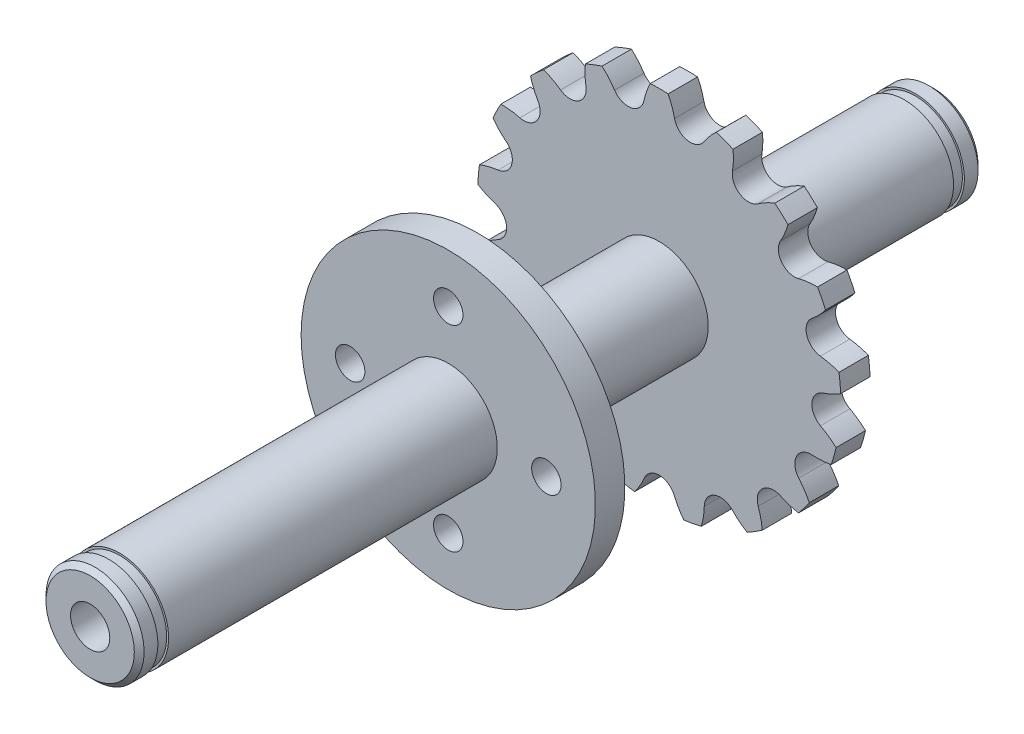
SolidWorks part; units mm, degrees
material "合金钢"
ref_plane "前视基准面" through (0, 0, 0) normal (0, 0, 1) x (1, 0, 0)
ref_plane "上视基准面" through (0, 0, 0) normal (0, 1, 0) x (1, 0, 0)
ref_plane "右视基准面" through (0, 0, 0) normal (1, 0, 0) x (0, 0, -1)
sketch "草图1" plane through (0, 0, 0) normal (0, 0, 1) x (1, 0, 0)
  line L0 (0, 15.63) -> (0, 27.7184) construction
  line L1 (2.872, 15.3639) -> (4.904, 26.2342) construction
  line L2 (-2.872, 15.3639) -> (-4.904, 26.2342) construction
  line L3 (-3.175, 16.9847) -> (3.175, 16.9847) construction
  line L4 (3.175, 16.9847) -> (-13.356, 13.4532) construction
  line L5 (3.175, 16.9847) -> (-5.7966, 15.0682) construction
  circle A0 centre (0, 0) radius 17.279 construction
  arc A1 (-11.7798, 14.2714) -> (-13.1236, 13.0463) centre (0, 0) ccw
  circle A2 centre (0, 0) radius 15.63 construction
  arc A5 (1.5624, 16.6403) -> (0.9092, 18.4826) centre (-5.7966, 15.0682) ccw
  arc A6 (1.5624, 16.6403) -> (2.872, 15.3639) centre (3.175, 16.9847) ccw
  arc A7 (-1.5624, 16.6403) -> (-0.9092, 18.4826) centre (5.7966, 15.0682) cw
  arc A8 (-1.5624, 16.6403) -> (-2.872, 15.3639) centre (-3.175, 16.9847) cw
  arc A9 (4.5542, 16.081) -> (5.8289, 17.563) centre (10.8484, 11.9567) cw
  arc A10 (4.5542, 16.081) -> (2.872, 15.3639) centre (3.175, 16.9847) cw
  arc A11 (7.4681, 14.9522) -> (8.2281, 13.2889) centre (9.0962, 14.6909) ccw
  arc A12 (7.4681, 14.9522) -> (7.5245, 16.9061) centre (0.0381, 16.1446) ccw
  arc A13 (10.0558, 13.3499) -> (11.7798, 14.2714) centre (14.4351, 7.2304) cw
  arc A14 (10.0558, 13.3499) -> (8.2281, 13.2889) centre (9.0962, 14.6909) cw
  arc A15 (12.3651, 11.2447) -> (12.473, 9.4192) centre (13.7889, 10.4129) ccw
  arc A16 (12.3651, 11.2447) -> (13.1236, 13.0463) centre (5.8676, 15.0406) ccw
  arc A17 (14.1993, 8.8158) -> (16.1397, 9.0523) centre (16.0722, 1.5276) cw
  arc A18 (14.1993, 8.8158) -> (12.473, 9.4192) centre (13.7889, 10.4129) cw
  arc A19 (15.5922, 6.0186) -> (15.0333, 4.2774) centre (16.6193, 4.7286) ccw
  arc A20 (15.5922, 6.0186) -> (16.9503, 7.4245) centre (10.9047, 11.9053) ccw
  arc A21 (16.4251, 3.0911) -> (18.3199, 2.6107) centre (15.5387, -4.3815) cw
  arc A22 (16.4251, 3.0911) -> (15.0333, 4.2774) centre (16.6193, 4.7286) cw
  arc A23 (16.7134, -0.0204) -> (15.5633, -1.4422) centre (17.2052, -1.5943) ccw
  arc A24 (16.7134, -0.0204) -> (18.4877, 0.8) centre (14.469, 7.1622) ccw
  arc A25 (16.4326, -3.051) -> (18.0259, -4.1835) centre (12.9066, -9.6989) cw
  arc A26 (16.4326, -3.051) -> (15.5633, -1.4422) centre (17.2052, -1.5943) cw
  arc A27 (15.5774, -6.0566) -> (13.9914, -6.9669) centre (15.4675, -7.7019) ccw
  arc A28 (15.5774, -6.0566) -> (17.5283, -5.9325) centre (16.0792, 1.4517) ccw
  arc A29 (14.2208, -8.7811) -> (15.2974, -10.4127) centre (8.5314, -13.7064) cw
  arc A30 (14.2208, -8.7811) -> (13.9914, -6.9669) centre (15.4675, -7.7019) cw
  arc A31 (12.3376, -11.2748) -> (10.5299, -11.5507) centre (11.6408, -12.7693) ccw
  arc A32 (12.3376, -11.2748) -> (14.2015, -11.8639) centre (15.5179, -4.4548) ccw
  arc A33 (10.0884, -13.3253) -> (10.5029, -15.2356) centre (3.004, -15.8627) cw
  arc A34 (10.0884, -13.3253) -> (10.5299, -11.5507) centre (11.6408, -12.7693) cw
  arc A35 (7.4316, -14.9703) -> (5.6462, -14.5745) centre (6.2419, -16.1121) ccw
  arc A36 (7.4316, -14.9703) -> (8.9568, -16.1929) centre (12.8607, -9.7597) ccw
  arc A37 (4.5935, -16.0698) -> (4.2899, -18.0009) centre (-2.9291, -15.8767) cw
  arc A38 (4.5935, -16.0698) -> (5.6462, -14.5745) centre (6.2419, -16.1121) cw
  arc A39 (1.5218, -16.644) -> (0, -15.63) centre (0, -17.279) ccw
  arc A40 (1.5218, -16.644) -> (2.5024, -18.335) centre (8.4666, -13.7465) ccw
  arc A41 (-1.5218, -16.644) -> (-2.5024, -18.335) centre (-8.4666, -13.7465) cw
  arc A42 (-1.5218, -16.644) -> (0, -15.63) centre (0, -17.279) cw
  arc A43 (-4.5935, -16.0698) -> (-5.6462, -14.5745) centre (-6.2419, -16.1121) ccw
  arc A44 (-4.5935, -16.0698) -> (-4.2899, -18.0009) centre (2.9291, -15.8767) ccw
  arc A45 (-7.4316, -14.9703) -> (-8.9568, -16.1929) centre (-12.8607, -9.7597) cw
  arc A46 (-7.4316, -14.9703) -> (-5.6462, -14.5745) centre (-6.2419, -16.1121) cw
  arc A47 (-10.0884, -13.3253) -> (-10.5299, -11.5507) centre (-11.6408, -12.7693) ccw
  arc A48 (-10.0884, -13.3253) -> (-10.5029, -15.2356) centre (-3.004, -15.8627) ccw
  arc A49 (-12.3376, -11.2748) -> (-14.2015, -11.8639) centre (-15.5179, -4.4548) cw
  arc A50 (-12.3376, -11.2748) -> (-10.5299, -11.5507) centre (-11.6408, -12.7693) cw
  arc A51 (-14.2208, -8.7811) -> (-13.9914, -6.9669) centre (-15.4675, -7.7019) ccw
  arc A52 (-14.2208, -8.7811) -> (-15.2974, -10.4127) centre (-8.5314, -13.7064) ccw
  arc A53 (-15.5774, -6.0566) -> (-17.5283, -5.9325) centre (-16.0792, 1.4517) cw
  arc A54 (-15.5774, -6.0566) -> (-13.9914, -6.9669) centre (-15.4675, -7.7019) cw
  arc A55 (-16.4326, -3.051) -> (-15.5633, -1.4422) centre (-17.2052, -1.5943) ccw
  arc A56 (-16.4326, -3.051) -> (-18.0259, -4.1835) centre (-12.9066, -9.6989) ccw
  arc A57 (-16.7134, -0.0204) -> (-18.4877, 0.8) centre (-14.469, 7.1622) cw
  arc A58 (-16.7134, -0.0204) -> (-15.5633, -1.4422) centre (-17.2052, -1.5943) cw
  arc A59 (-16.4251, 3.0911) -> (-15.0333, 4.2774) centre (-16.6193, 4.7286) ccw
  arc A60 (-16.4251, 3.0911) -> (-18.3199, 2.6107) centre (-15.5387, -4.3815) ccw
  arc A61 (-15.5922, 6.0186) -> (-16.9503, 7.4245) centre (-10.9047, 11.9053) cw
  arc A62 (-15.5922, 6.0186) -> (-15.0333, 4.2774) centre (-16.6193, 4.7286) cw
  arc A63 (-14.1993, 8.8158) -> (-12.473, 9.4192) centre (-13.7889, 10.4129) ccw
  arc A64 (-14.1993, 8.8158) -> (-16.1397, 9.0523) centre (-16.0722, 1.5276) ccw
  arc A65 (-12.3651, 11.2447) -> (-13.1236, 13.0463) centre (-5.8676, 15.0406) cw
  arc A66 (-12.3651, 11.2447) -> (-12.473, 9.4192) centre (-13.7889, 10.4129) cw
  arc A67 (-10.0558, 13.3499) -> (-8.2281, 13.2889) centre (-9.0962, 14.6909) ccw
  arc A68 (-10.0558, 13.3499) -> (-11.7798, 14.2714) centre (-14.4351, 7.2304) ccw
  arc A69 (-7.4681, 14.9522) -> (-7.5245, 16.9061) centre (-0.0381, 16.1446) cw
  arc A70 (-7.4681, 14.9522) -> (-8.2281, 13.2889) centre (-9.0962, 14.6909) cw
  arc A71 (-4.5542, 16.081) -> (-2.872, 15.3639) centre (-3.175, 16.9847) ccw
  arc A72 (-4.5542, 16.081) -> (-5.8289, 17.563) centre (-10.8484, 11.9567) ccw
  arc A73 (-5.8289, 17.563) -> (-7.5245, 16.9061) centre (0, 0) ccw
  arc A74 (0.9092, 18.4826) -> (-0.9092, 18.4826) centre (0, 0) ccw
  arc A75 (7.5245, 16.9061) -> (5.8289, 17.563) centre (0, 0) ccw
  arc A76 (13.1236, 13.0463) -> (11.7798, 14.2714) centre (0, 0) ccw
  arc A77 (16.9503, 7.4245) -> (16.1397, 9.0523) centre (0, 0) ccw
  arc A78 (18.4877, 0.8) -> (18.3199, 2.6107) centre (0, 0) ccw
  arc A79 (17.5283, -5.9325) -> (18.0259, -4.1835) centre (0, 0) ccw
  arc A80 (14.2015, -11.8639) -> (15.2974, -10.4127) centre (0, 0) ccw
  arc A81 (8.9568, -16.1929) -> (10.5029, -15.2356) centre (0, 0) ccw
  arc A82 (2.5024, -18.335) -> (4.2899, -18.0009) centre (0, 0) ccw
  arc A83 (-4.2899, -18.0009) -> (-2.5024, -18.335) centre (0, 0) ccw
  arc A84 (-10.5029, -15.2356) -> (-8.9568, -16.1929) centre (0, 0) ccw
  arc A85 (-15.2974, -10.4127) -> (-14.2015, -11.8639) centre (0, 0) ccw
  arc A86 (-18.0259, -4.1835) -> (-17.5283, -5.9325) centre (0, 0) ccw
  arc A87 (-18.3199, 2.6107) -> (-18.4877, 0.8) centre (0, 0) ccw
  arc A88 (-16.1397, 9.0523) -> (-16.9503, 7.4245) centre (0, 0) ccw
  point P181 (0, 0)
  dimension "D1" = 34.5579
  dimension "D2" = 37.01
  dimension "D3" = 31.26
  dimension "D5" = 67.353
  dimension "D6" = 9.174
  dimension "D7" = 17
  dimension "D4" = 10.588
extrude "凸台-拉伸2" add sketch "草图1" along normal blind 3
sketch "草图2" plane through (0, 0, 0) normal (0, 0, -1) x (-1, 0, 0)
  circle A0 centre (0, 0) radius 5
  dimension "D1" = 10
extrude "凸台-拉伸3" add sketch "草图2" along normal blind 25
sketch "草图3" plane through (0, 0, 3) normal (0, 0, 1) x (1, 0, 0)
  circle A0 centre (0, 0) radius 5
  dimension "D1" = 10
extrude "凸台-拉伸4" add sketch "草图3" along normal blind 58
ref_plane "基准面1" through (0, 0, 21.5) normal (0, 0, -1) x (-1, 0, 0)
sketch "草图4" plane through (0, 0, 21.5) normal (0, 0, -1) x (-1, 0, 0)
  circle A0 centre (0, 0) radius 15
  dimension "D1" = 30
extrude "凸台-拉伸5" add sketch "草图4" against normal blind 3
sketch "草图5" plane through (0, 0, 24.5) normal (0, 0, 1) x (1, 0, 0)
  circle A0 centre (0, 0) radius 10 construction
  circle A1 centre (0, 10) radius 1.5
  circle A2 centre (10, 0) radius 1.5
  circle A3 centre (0, -10) radius 1.5
  circle A4 centre (-10, 0) radius 1.5
  point P14 (0, 0)
  dimension "D1" = 20
  dimension "D2" = 3
  dimension "D3" = 4
extrude "切除-拉伸1" cut sketch "草图5" against normal blind 3
sketch "草图7" plane through (0, 0, -25) normal (0, 0, -1) x (-1, 0, 0)
  circle A0 centre (0, 0) radius 2
  dimension "D1" = 4
extrude "切除-拉伸2" cut sketch "草图7" against normal blind 90
sketch "草图9" plane through (0, 0, 0) normal (0, 1, 0) x (1, 0, 0)
  line L0 (5, -61) -> (5, -58) construction
  line L2 (0, 25) -> (5, 25) construction
  line L7 (2, 25) -> (-2, 25) construction
  line L8 (5, 25) -> (-5, 25) construction
  line L9 (5, 25) -> (5, 22) construction
  line L10 (0, 25) -> (0, 19.564) construction
  line L11 (5, 22) -> (4.8, 22)
  line L12 (5, 22) -> (5, 23.1)
  line L13 (5, 23.1) -> (4.8, 23.1)
  line L14 (4.8, 22) -> (4.8, 23.1)
  line L15 (5, -61) -> (5, -24.5) construction
  line L17 (5, -58) -> (4.8, -58)
  line L18 (5, -58) -> (5, -59.1)
  line L19 (5, -59.1) -> (4.8, -59.1)
  line L20 (4.8, -58) -> (4.8, -59.1)
  dimension "D1" = 3
  dimension "D2" = 1.1
  dimension "D3" = 0.2
  dimension "D4" = 3
  dimension "D5" = 1.1
  dimension "D6" = 0.2
revolve "切除-旋转2" cut sketch "草图9" angle 360 about L10
chamfer "倒角3" distance 0.5 angle 45 2 edges at (-5, 0, -25) (5, 0, 61)
